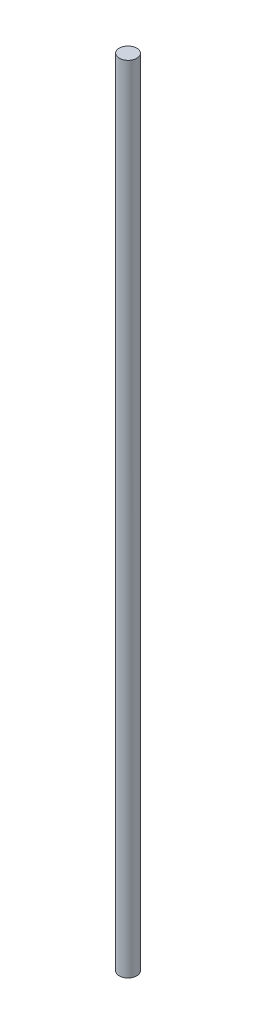
SolidWorks part; units mm, degrees
ref_plane "Plan de face" through (0, 0, 0) normal (0, 0, 1) x (1, 0, 0)
ref_plane "Plan de dessus" through (0, 0, 0) normal (0, 1, 0) x (1, 0, 0)
ref_plane "Plan de droite" through (0, 0, 0) normal (1, 0, 0) x (0, 0, -1)
sketch "Esquisse1" plane through (0, 0, 0) normal (0, 1, 0) x (1, 0, 0)
  circle A0 centre (0, 0) radius 4
  dimension "D1" = 8
extrude "Boss.-Extru.1" add sketch "Esquisse1" along normal up to surface (362 mm away)
